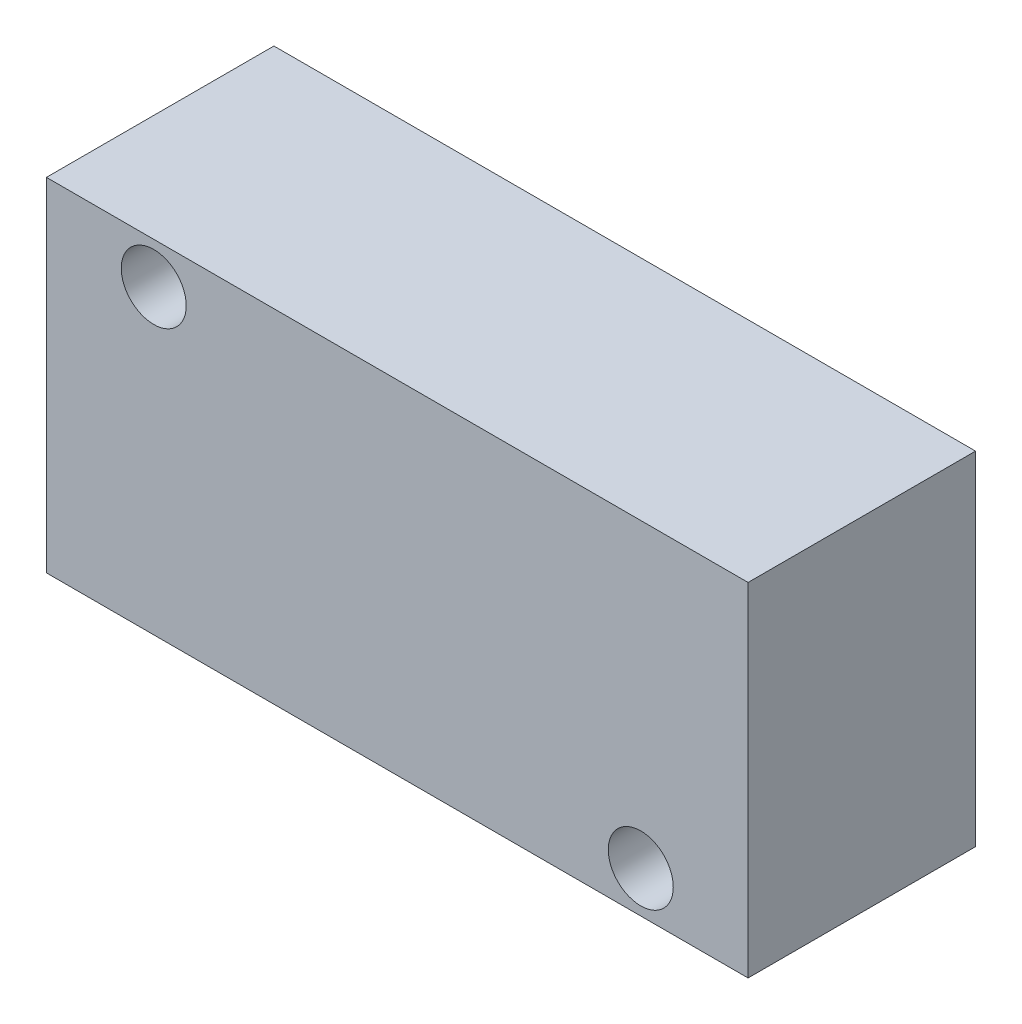
SolidWorks part; units mm, degrees
ref_plane "Ebene vorne" through (0, 0, 0) normal (0, 0, 1) x (1, 0, 0)
ref_plane "Ebene oben" through (0, 0, 0) normal (0, 1, 0) x (1, 0, 0)
ref_plane "Ebene rechts" through (0, 0, 0) normal (1, 0, 0) x (0, 0, -1)
sketch "Skizze1" plane through (0, 0, 0) normal (0, 0, 1) x (1, 0, 0)
  line L1 (21.59, 10.541) -> (-21.59, 10.541)
  line L2 (21.59, 10.541) -> (21.59, -10.541)
  line L3 (21.59, -10.541) -> (-21.59, -10.541)
  line L4 (-21.59, 10.541) -> (-21.59, -10.541)
  line L5 (21.59, 10.541) -> (-21.59, -10.541) construction
  line L6 (21.59, -10.541) -> (-21.59, 10.541) construction
  point P0 (0, 0)
  dimension "D1" = 21.082
  dimension "D2" = 43.18
extrude "Aufsatz-Linear austragen1" add sketch "Skizze1" along normal blind 14
sketch "Skizze2" plane through (0, 0, 14) normal (0, 0, 1) x (1, 0, 0)
  line L0 (14.986, -8.001) -> (-14.986, 8.001) construction
  line L1 (21.59, 10.541) -> (-21.59, 10.541) construction
  line L2 (-21.59, 10.541) -> (-21.59, -10.541) construction
  circle A0 centre (-14.986, 8.001) radius 2
  circle A1 centre (14.986, -8.001) radius 2
  point P3 (0, 0)
  dimension "D1" = 4
  dimension "D2" = 2.54
  dimension "D3" = 6.604
extrude "Schnitt-Linear austragen1" cut sketch "Skizze2" against normal through all
